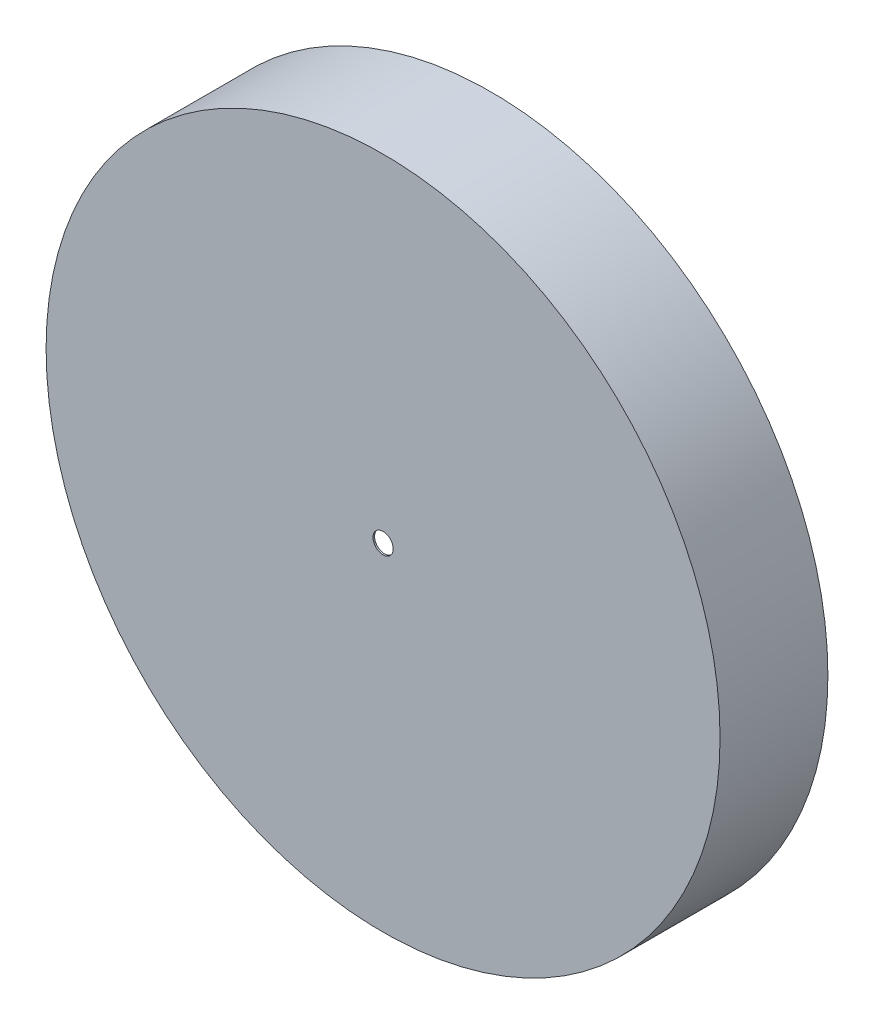
SolidWorks part; units mm, degrees
ref_plane "Front Plane" through (0, 0, 0) normal (0, 0, 1) x (1, 0, 0)
ref_plane "Top Plane" through (0, 0, 0) normal (0, 1, 0) x (1, 0, 0)
ref_plane "Right Plane" through (0, 0, 0) normal (1, 0, 0) x (0, 0, -1)
sketch "Sketch1" plane through (0, 0, 0) normal (0, 0, 1) x (1, 0, 0)
  circle A0 centre (0, 0) radius 250
  dimension "D1" = 500
extrude "Boss-Extrude1" add sketch "Sketch1" along normal blind 80
shell "Shell1" thickness 1.2
sketch "Sketch2" plane through (0, 0, 78.8) normal (0, 0, -1) x (-1, 0, 0)
  circle A0 centre (0, 0) radius 7.5
  dimension "D1" = 15
extrude "Cut-Extrude1" cut sketch "Sketch2" against normal blind 10
